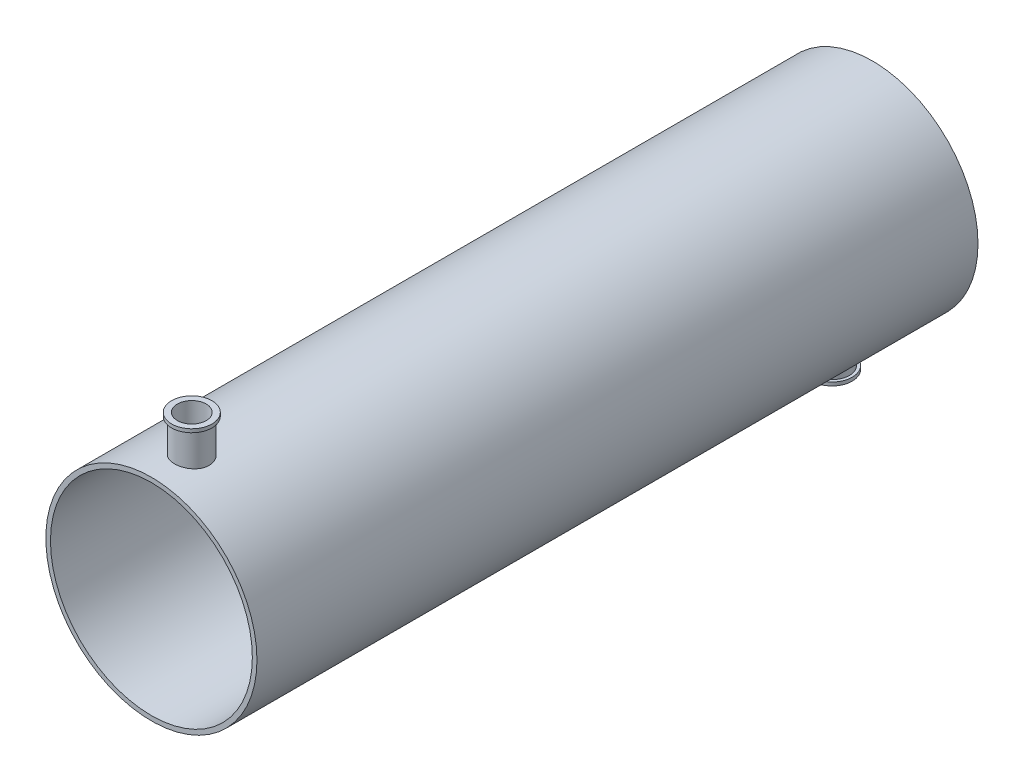
SolidWorks part; units mm, degrees
material "Steel Stainless 302"
ref_plane "Front Plane" through (0, 0, 0) normal (0, 0, 1) x (1, 0, 0)
ref_plane "Top Plane" through (0, 0, 0) normal (0, 1, 0) x (1, 0, 0)
ref_plane "Right Plane" through (0, 0, 0) normal (1, 0, 0) x (0, 0, -1)
sketch "Sketch1" plane through (0, 0, 0) normal (0, 0, 1) x (1, 0, 0)
  circle A0 centre (0, 0) radius 444.5
  circle A1 centre (0, 0) radius 464.82
  dimension "D1" = 929.64
  dimension "D2" = 889
extrude "Boss-Extrude1" add sketch "Sketch1" against normal blind 3175
sketch "Sketch2" plane through (0, 0, 0) normal (0, 1, 0) x (1, 0, 0)
  circle A0 centre (0, 177.8) radius 63.5
  circle A1 centre (0, 177.8) radius 76.2
  dimension "D1" = 127
  dimension "D3" = 177.8
  dimension "D2" = 12.7
extrude "Boss-Extrude2" add sketch "Sketch2" along normal blind 254 from offset 369.2906
sketch "Sketch3" plane through (0, 369.2906, 0) normal (0, -1, 0) x (1, 0, 0)
  circle A0 centre (0, -177.8) radius 63.5 construction
  circle A3 centre (0, -177.8) radius 63.5
extrude "Cut-Extrude1" cut sketch "Sketch3" against normal blind 742.4928
sketch "Sketch4" plane through (0, 623.2906, 0) normal (0, 1, 0) x (1, 0, 0)
  circle A0 centre (0, 177.8) radius 88.9
  circle A1 centre (0, 177.8) radius 76.2
  circle A2 centre (0, 177.8) radius 76.2
  dimension "D2" = 177.8
  dimension "D1" = 0
extrude "Boss-Extrude3" add sketch "Sketch4" against normal blind 15.24
sketch "Sketch5" plane through (0, 0, 0) normal (0, 1, 0) x (1, 0, 0)
  line L0 (0, 3175) -> (0, 0) construction
  line L1 (444.5, 3175) -> (-444.5, 3175) construction
  circle A0 centre (0, 2997.2) radius 63.5
  circle A1 centre (0, 2997.2) radius 76.2
  dimension "D1" = 127
  dimension "D2" = 12.7
  dimension "D3" = 177.8
extrude "Boss-Extrude4" add sketch "Sketch5" against normal blind 254 from offset 369.2906 offset against normal yes
sketch "Sketch6" plane through (0, -623.2906, 0) normal (0, -1, 0) x (1, 0, 0)
  circle A0 centre (0, -2997.2) radius 63.5 construction
  circle A1 centre (0, -2997.2) radius 63.5
extrude "Cut-Extrude2" cut sketch "Sketch6" against normal blind 736.6
sketch "Sketch7" plane through (0, 0, 0) normal (0, 0, 1) x (1, 0, 0)
  circle A0 centre (0, 0) radius 444.5 construction
  circle A1 centre (0, 0) radius 444.5
extrude "Cut-Extrude3" cut sketch "Sketch7" against normal up to surface (3175 mm away) up to face at (444.5, 0, -3175)
sketch "Sketch9" plane through (0, -623.2906, 0) normal (0, -1, 0) x (1, 0, 0)
  circle A1 centre (0, -2997.2) radius 88.9
  circle A2 centre (0, -2997.2) radius 76.2 construction
  circle A3 centre (0, -2997.2) radius 76.2
  dimension "D1" = 177.8
extrude "Boss-Extrude5" add sketch "Sketch9" against normal blind 15.24
